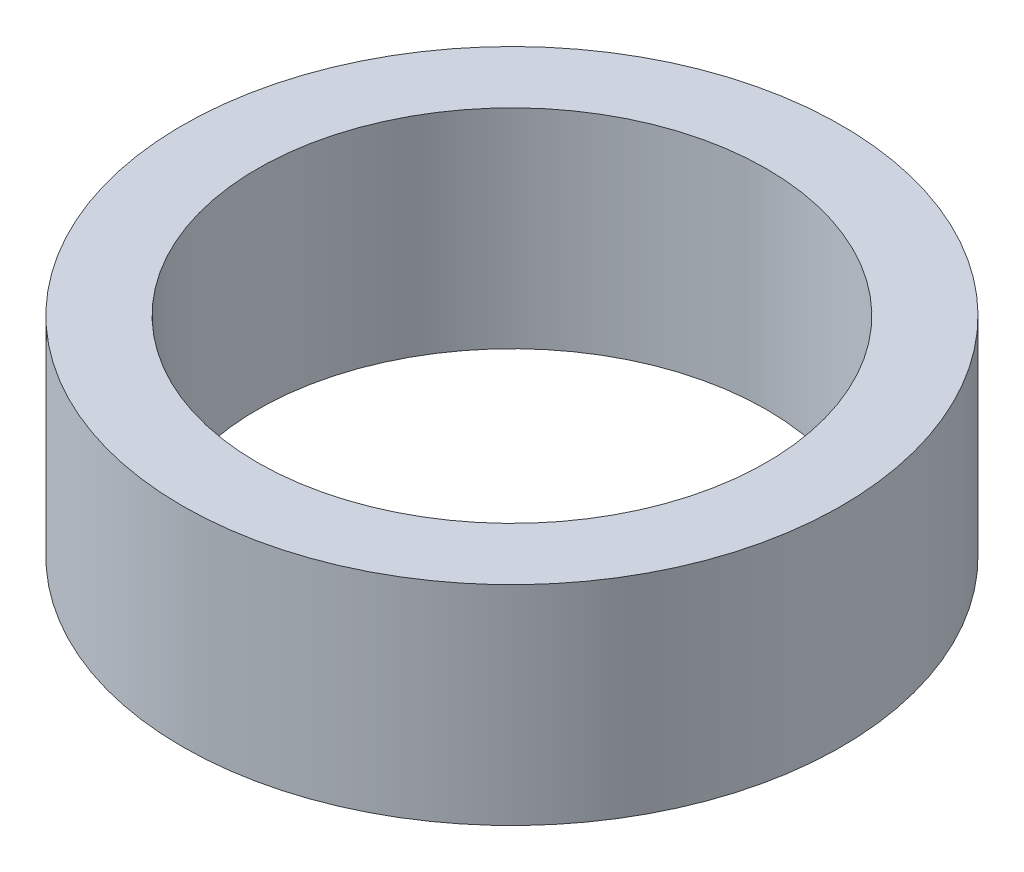
SolidWorks part; units mm, degrees
ref_plane "Front Plane" through (0, 0, 0) normal (0, 0, 1) x (1, 0, 0)
ref_plane "Top Plane" through (0, 0, 0) normal (0, 1, 0) x (1, 0, 0)
ref_plane "Right Plane" through (0, 0, 0) normal (1, 0, 0) x (0, 0, -1)
sketch "Sketch1" plane through (0, 0, 0) normal (0, 1, 0) x (1, 0, 0)
  circle A0 centre (0, 0) radius 6.1
  circle A1 centre (0, 0) radius 7.9
  dimension "D1" = 12.2
  dimension "D2" = 1.8
extrude "Boss-Extrude1" add sketch "Sketch1" along normal blind 5
